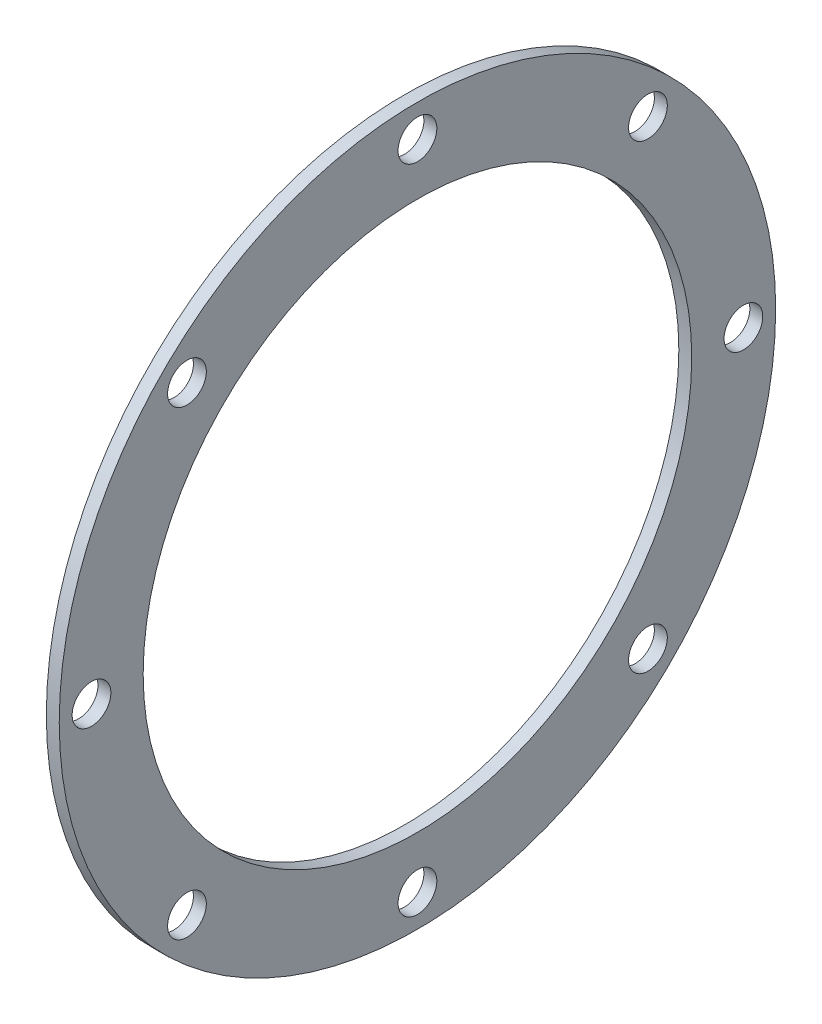
SolidWorks part; units mm, degrees
material "1023 Karbon Çeliği Levha (SS)"
ref_plane "Front Plane" through (0, 0, 0) normal (0, 0, 1) x (1, 0, 0)
ref_plane "Top Plane" through (0, 0, 0) normal (0, 1, 0) x (1, 0, 0)
ref_plane "Right Plane" through (0, 0, 0) normal (1, 0, 0) x (0, 0, -1)
sketch "Sketch1" plane through (0, 0, 0) normal (1, 0, 0) x (0, 0, -1)
  circle A0 centre (0, 0) radius 42.495
  circle A1 centre (0, 0) radius 55.5
  dimension "D1" = 111
  dimension "D2" = 84.99
extrude "Boss-Extrude1" add sketch "Sketch1" along normal blind 2
sketch "Sketch2" plane through (0, 0, 0) normal (-1, 0, 0) x (0, 0, 1)
  circle A0 centre (0, 0) radius 50.5 construction
  circle A4 centre (0, 50.5) radius 3
  circle A5 centre (35.7089, 35.7089) radius 3
  circle A6 centre (50.5, 0) radius 3
  circle A7 centre (35.7089, -35.7089) radius 3
  circle A8 centre (0, -50.5) radius 3
  circle A9 centre (-35.7089, -35.7089) radius 3
  circle A10 centre (-50.5, 0) radius 3
  circle A11 centre (-35.7089, 35.7089) radius 3
  point P21 (0, 0)
  dimension "D1" = 101
  dimension "D2" = 6
  dimension "D3" = 8
extrude "Cut-Extrude1" cut sketch "Sketch2" against normal blind 15
